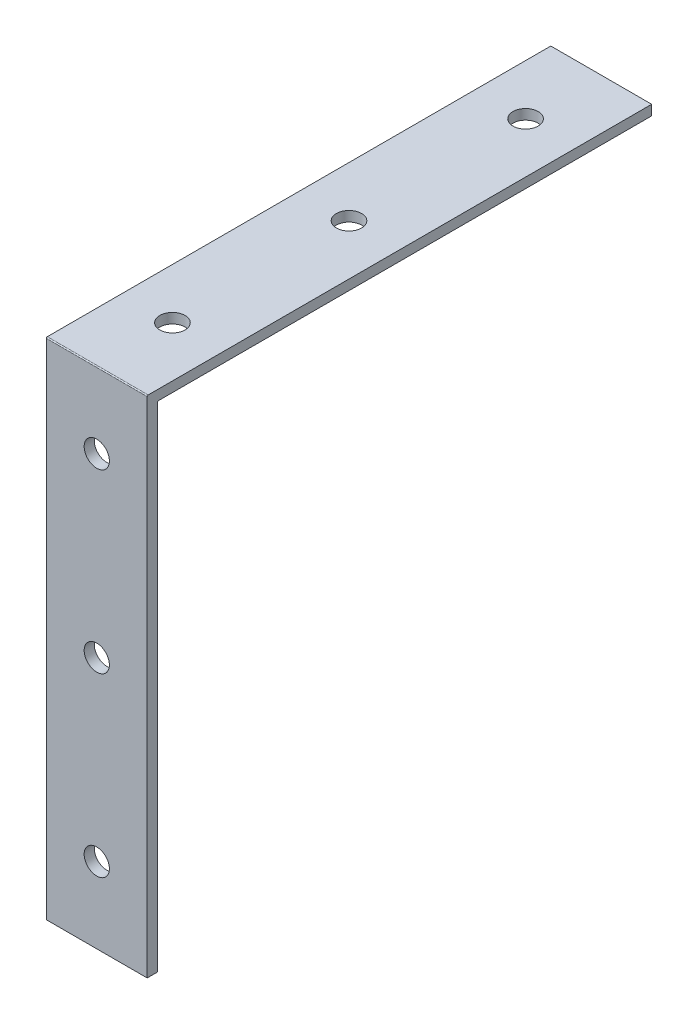
SolidWorks part; units mm, degrees
ref_plane "Front Plane" through (0, 0, 0) normal (0, 0, 1) x (1, 0, 0)
ref_plane "Top Plane" through (0, 0, 0) normal (0, 1, 0) x (1, 0, 0)
ref_plane "Right Plane" through (0, 0, 0) normal (1, 0, 0) x (0, 0, -1)
ref_plane "Plane1"
sketch "Sketch1" plane through (0, 0, 0) normal (1, 0, 0) x (0, 1, 0)
  line L0 (0, -100) -> (0, -0.2)
  line L1 (-0.2, 0) -> (-100, 0)
  line L2 (-100, 0) -> (-100, -2)
  line L3 (-100, -2) -> (-2.2, -2)
  line L4 (-2, -2.2) -> (-2, -100)
  line L5 (-2, -100) -> (0, -100)
  arc A0 (0, -0.2) -> (-0.2, 0) centre (-0.2, -0.2) ccw
  arc A1 (-2, -2.2) -> (-2.2, -2) centre (-2.2, -2.2) ccw
  dimension "D4" = 0.2
  dimension "D1" = 100
  dimension "D2" = 2
  dimension "D3" = 2
extrude "Extrusion1" add sketch "Sketch1" along normal blind 20
hole_wizard "Hole1" positions "Sketch3" profile "Sketch2" legacy end condition through all
sketch "Sketch3" plane through (0, 0, 0) normal (0, 1, 0) x (1, 0, 0)
  point P1 (10, 15)
  point P2 (10, 50)
  point P3 (10, 85)
sketch "Sketch2" plane through (10, 0, -15) normal (1, 0, 0) x (0, 0, 1)
  line L0 (0, 0) -> (0, 100)
  line L1 (0, 100) -> (2.5, 100)
  line L2 (2.5, 100) -> (2.5, 0)
  line L3 (2.5, 0) -> (0, 0)
  line L4 (0, 110) -> (0, -10) construction
  dimension "Diameter" = 5
  dimension "Depth" = 100
hole_wizard "Hole2" positions "Sketch5" profile "Sketch4" legacy end condition through all
sketch "Sketch5" plane through (0, 0, 0) normal (0, 0, 1) x (1, 0, 0)
  point P1 (10, -85)
  point P2 (10, -50)
  point P3 (10, -15)
sketch "Sketch4" plane through (10, -85, 0) normal (1, 0, 0) x (0, -1, 0)
  line L0 (0, 0) -> (0, 100)
  line L1 (0, 100) -> (2.5, 100)
  line L2 (2.5, 100) -> (2.5, 0)
  line L3 (2.5, 0) -> (0, 0)
  line L4 (0, 110) -> (0, -10) construction
  dimension "Diameter" = 5
  dimension "Depth" = 100
